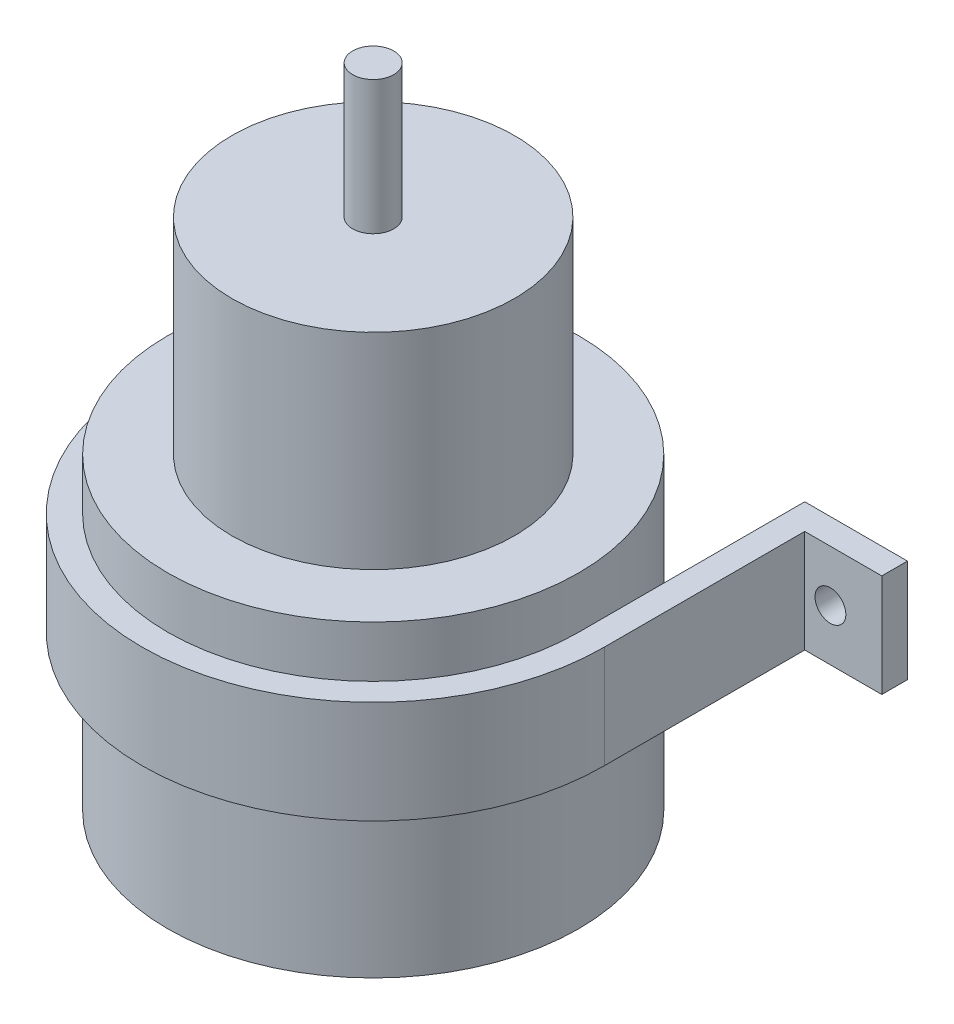
SolidWorks part; units mm, degrees
ref_plane "Front Plane" through (0, 0, 0) normal (0, 0, 1) x (1, 0, 0)
ref_plane "Top Plane" through (0, 0, 0) normal (0, 1, 0) x (1, 0, 0)
ref_plane "Right Plane" through (0, 0, 0) normal (1, 0, 0) x (0, 0, -1)
sketch "Sketch1" plane through (0, 0, 0) normal (0, 1, 0) x (1, 0, 0)
  circle A0 centre (0, 0) radius 20
  dimension "D1" = 40
extrude "Boss-Extrude1" add sketch "Sketch1" along normal blind 30
sketch "Sketch2" plane through (0, 30, 0) normal (0, 1, 0) x (1, 0, 0)
  circle A0 centre (0, 0) radius 13.75
  dimension "D1" = 27.5
extrude "Boss-Extrude2" add sketch "Sketch2" along normal blind 20
sketch "Sketch3" plane through (0, 50, 0) normal (0, 1, 0) x (1, 0, 0)
  circle A0 centre (0, 0) radius 2
  dimension "D1" = 4
extrude "Boss-Extrude3" add sketch "Sketch3" along normal blind 13
ref_plane "Plane1" through (0, 25, 0) normal (0, 1, 0) x (1, 0, 0)
sketch "Sketch4" plane through (0, 25, 0) normal (0, 1, 0) x (1, 0, 0)
  line L0 (-20, 0) -> (-20, 22)
  line L1 (-20, 22) -> (-30, 22)
  line L2 (0, -22) -> (0, 22) construction
  line L3 (20, 0) -> (20, 22)
  line L4 (20, 22) -> (30, 22)
  arc A0 (-20, 0) -> (20, 0) centre (0, 0) ccw
  dimension "D1" = 22
  dimension "D2" = 10
extrude "Extrude-Thin2" add sketch "Sketch4" against normal blind 10 thin thin type one direction wall 2.5
sketch "Sketch6" plane through (0, 0, -22) normal (0, 0, -1) x (-1, 0, 0)
  line L2 (-30, 15) -> (-30, 25) construction
  line L3 (24.475, 25) -> (-24.475, 25) construction
  line L4 (0, 22) -> (0, -22) construction
  circle A0 centre (-25, 20) radius 1.5
  circle A1 centre (25, 20) radius 1.5
  dimension "D1" = 3
  dimension "D2" = 5
  dimension "D3" = 5
extrude "Cut-Extrude1" cut sketch "Sketch6" against normal blind 10
